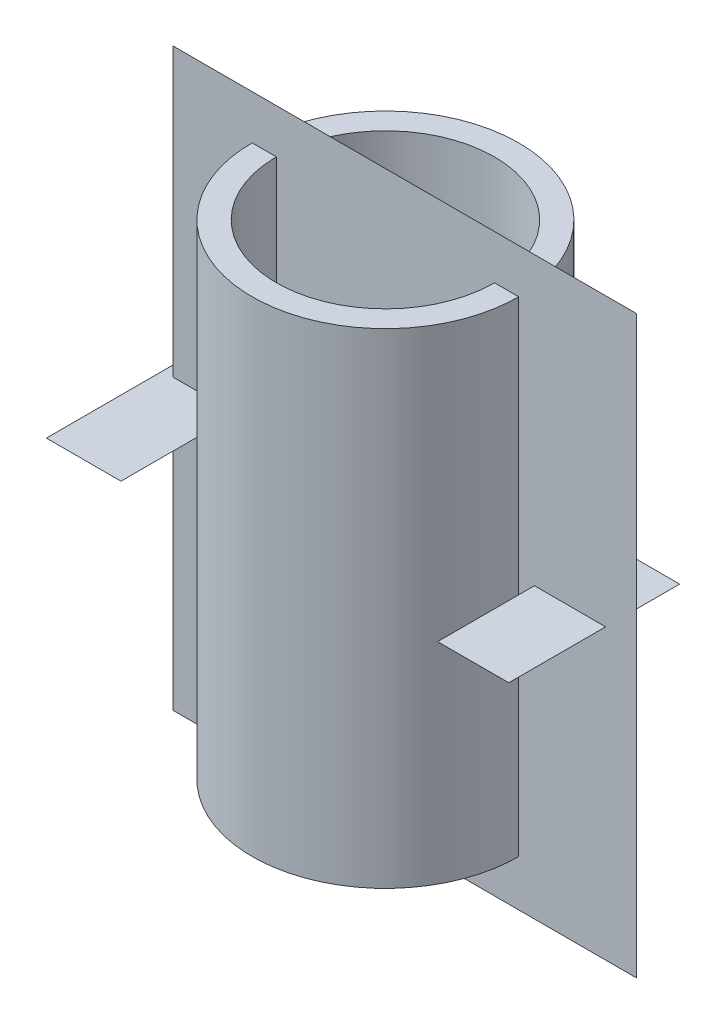
SolidWorks part; units mm, degrees
ref_plane "Спереди" through (0, 0, 0) normal (0, 0, 1) x (1, 0, 0)
ref_plane "Сверху" through (0, 0, 0) normal (0, 1, 0) x (1, 0, 0)
ref_plane "Справа" through (0, 0, 0) normal (1, 0, 0) x (0, 0, -1)
sketch "Эскиз1" plane through (0, 0, 0) normal (0, 0, 1) x (1, 0, 0)
  line L0 (0, -110.6031) -> (0, 130.0787) construction
  line L1 (45, 100) -> (55, 100)
  line L2 (45, 100) -> (45, -100)
  line L3 (45, -100) -> (55, -100)
  line L4 (55, 100) -> (55, -100)
  point P4 (45, 0)
  dimension "D1" = 10
  dimension "D2" = 200
  dimension "D3" = 45
revolve "Повернуть1" add sketch "Эскиз1" angle 360 about L0
sketch "Эскиз2_fr" plane through (0, 0, 0) normal (0, 0, 1) x (1, 0, 0)
  line L1 (-87.5897, 118.3128) -> (103.6191, 118.3128)
  line L2 (-87.5897, 118.3128) -> (-87.5897, -119.0761)
  line L3 (-87.5897, -119.0761) -> (103.6191, -119.0761)
  line L4 (103.6191, 118.3128) -> (103.6191, -119.0761)
surface "Поверхность-Заполнить1" sketch "Эскиз2_fr"
sketch "Эскиз3" plane through (0, 0, 0) normal (0, 1, 0) x (1, 0, 0)
  line L1 (61.468, 30.5447) -> (90.838, 30.5447)
  line L2 (61.468, 30.5447) -> (61.468, -39.9431)
  line L3 (61.468, -39.9431) -> (90.838, -39.9431)
  line L4 (90.838, 30.5447) -> (90.838, -39.9431)
  line L5 (-91.9605, 36.6537) -> (-61.1808, 36.6537)
  line L6 (-91.9605, 36.6537) -> (-91.9605, -47.9317)
  line L7 (-91.9605, -47.9317) -> (-61.1808, -47.9317)
  line L8 (-61.1808, 36.6537) -> (-61.1808, -47.9317)
surface "Поверхность-Плоскость1" sketch "Эскиз3"
